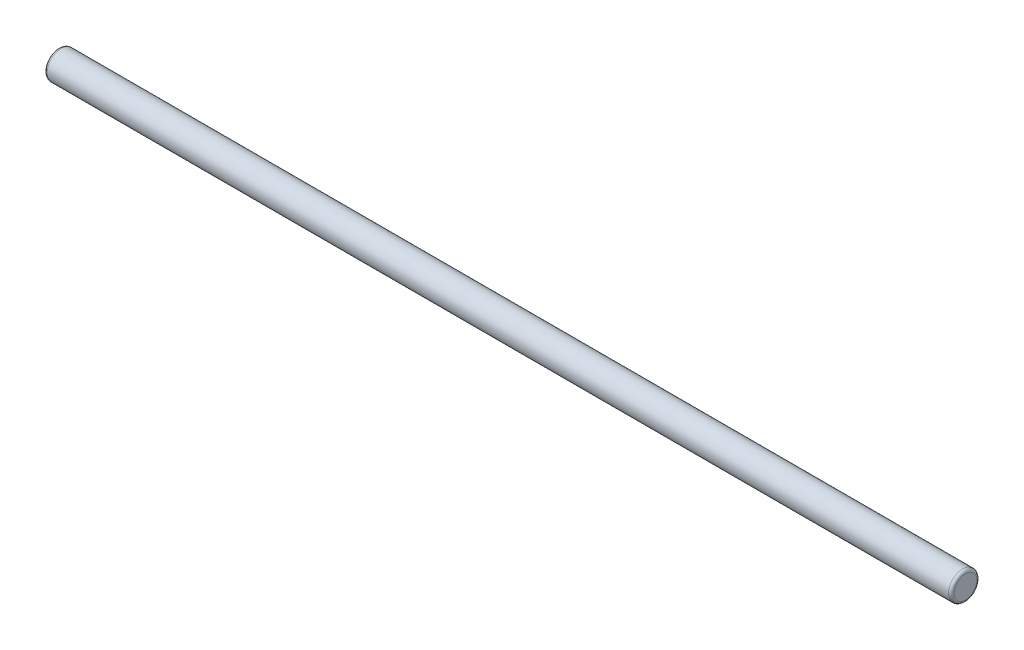
SolidWorks part; units mm, degrees
ref_plane "Front Plane" through (0, 0, 0) normal (0, 0, 1) x (1, 0, 0)
ref_plane "Top Plane" through (0, 0, 0) normal (0, 1, 0) x (1, 0, 0)
ref_plane "Right Plane" through (0, 0, 0) normal (1, 0, 0) x (0, 0, -1)
sketch "Sketch1" plane through (0, 0, 0) normal (1, 0, 0) x (0, 0, -1)
  circle A0 centre (0, 0) radius 12.7
  dimension "D1" = 25.4
extrude "Boss-Extrude1" add sketch "Sketch1" against normal blind 812.8
fillet "Fillet1" radius 2.54 2 edges at (0, 0, -12.7) (-812.8, 0, -12.7)
